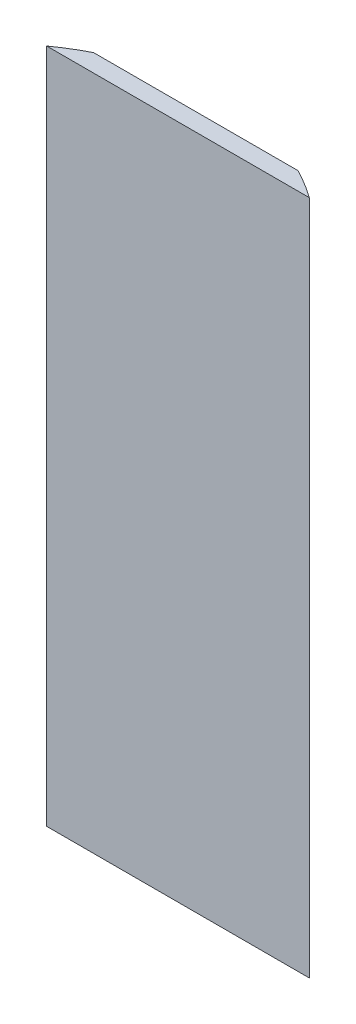
SolidWorks part; units mm, degrees
material "6061 Alloy"
ref_plane "Front Plane" through (0, 0, 0) normal (0, 0, 1) x (1, 0, 0)
ref_plane "Top Plane" through (0, 0, 0) normal (0, 1, 0) x (1, 0, 0)
ref_plane "Right Plane" through (0, 0, 0) normal (1, 0, 0) x (0, 0, -1)
sketch "Sketch1" plane through (0, 0, 0) normal (0, 1, 0) x (1, 0, 0)
  line L0 (-11.8458, 16.51) -> (11.8458, 16.51)
  line L1 (-9.2154, 18.1102) -> (9.2154, 18.1102)
  arc A0 (-11.8458, 16.51) -> (-9.2154, 18.1102) centre (0, 0) cw
  arc A1 (11.8458, 16.51) -> (9.2154, 18.1102) centre (0, 0) ccw
  dimension "D1" = 20.32
  dimension "D2" = 20.32
  dimension "D3" = 16.51
  dimension "D4" = 1.6002
extrude "Boss-Extrude1" add sketch "Sketch1" along normal blind 60.96
